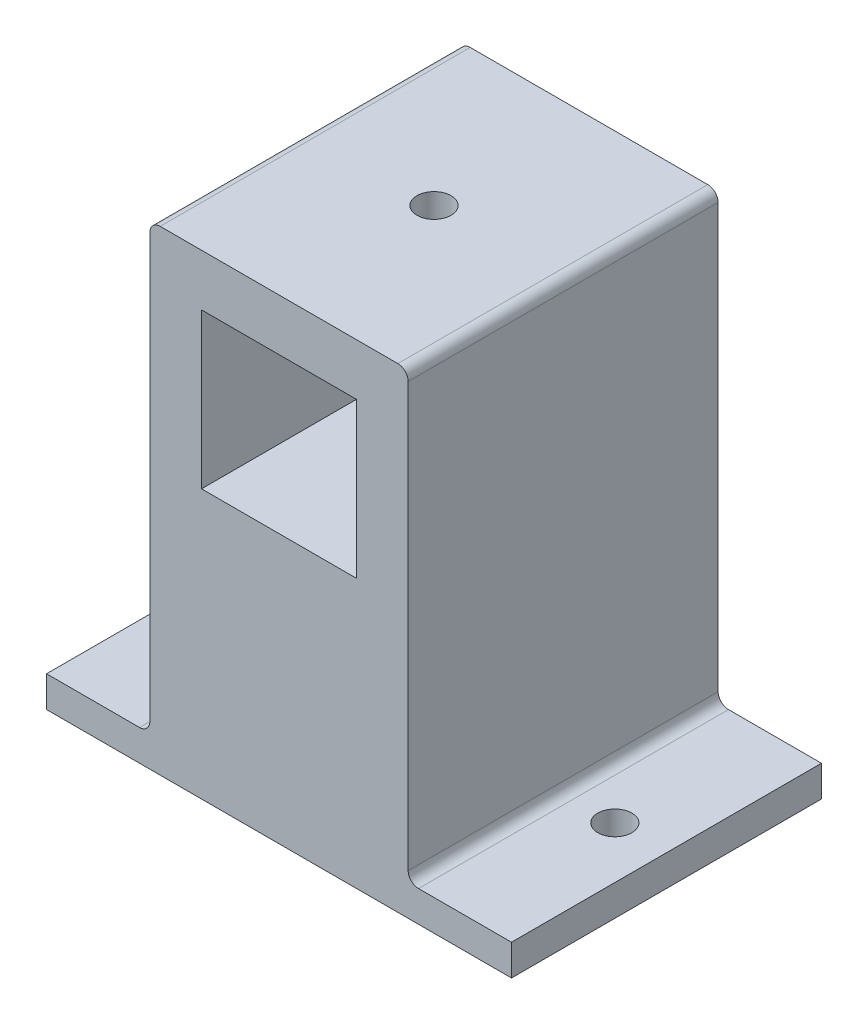
SolidWorks part; units mm, degrees
ref_plane "前视基准面" through (0, 0, 0) normal (0, 0, 1) x (1, 0, 0)
ref_plane "上视基准面" through (0, 0, 0) normal (0, 1, 0) x (1, 0, 0)
ref_plane "右视基准面" through (0, 0, 0) normal (1, 0, 0) x (0, 0, -1)
sketch "草图1" plane through (0, 0, 0) normal (0, 0, 1) x (1, 0, 0)
  line L1 (-7.5, -7.5) -> (7.5, -7.5)
  line L2 (-7.5, -7.5) -> (-7.5, 7.5)
  line L3 (-7.5, 7.5) -> (7.5, 7.5)
  line L4 (7.5, -7.5) -> (7.5, 7.5)
  line L5 (-7.5, -7.5) -> (7.5, 7.5) construction
  line L6 (-7.5, 7.5) -> (7.5, -7.5) construction
  line L7 (-12.5, -12.5) -> (12.5, -12.5)
  line L8 (-12.5, -12.5) -> (-12.5, 12.5)
  line L9 (-12.5, 12.5) -> (12.5, 12.5)
  line L10 (12.5, -12.5) -> (12.5, 12.5)
  line L11 (-12.5, -12.5) -> (12.5, 12.5) construction
  line L12 (-12.5, 12.5) -> (12.5, -12.5) construction
  point P0 (0, 0)
  point P6 (0, 0)
  dimension "D1" = 15
  dimension "D2" = 15
  dimension "D3" = 25
  dimension "D4" = 25
extrude "凸台-拉伸1" add sketch "草图1" along normal blind 30
sketch "草图2" plane through (0, 0, 30) normal (0, 0, 1) x (1, 0, 0)
  line L0 (0, 0) -> (0, -35.3965) construction
  line L2 (-12.5, -33.5) -> (12.5, -33.5)
  line L3 (-12.5, -33.5) -> (-12.5, -12.5)
  line L4 (-12.5, -12.5) -> (12.5, -12.5)
  line L5 (12.5, -33.5) -> (12.5, -12.5)
  line L6 (-12.5, -33.5) -> (12.5, -12.5) construction
  line L7 (-12.5, -12.5) -> (12.5, -33.5) construction
  line L8 (-22.5, -30.5) -> (22.5, -30.5)
  line L9 (-22.5, -30.5) -> (-22.5, -33.5)
  line L10 (-22.5, -33.5) -> (22.5, -33.5)
  line L11 (22.5, -30.5) -> (22.5, -33.5)
  line L12 (-22.5, -30.5) -> (22.5, -33.5) construction
  line L13 (-22.5, -33.5) -> (22.5, -30.5) construction
  point P3 (0, -23)
  point P9 (0, -32)
  line M8 (-12.5, -12.5) -> (12.5, -12.5)
  dimension "D1" = 21
  dimension "D2" = 3
  dimension "D3" = 45
extrude "凸台-拉伸2" add sketch "草图2" against normal blind 30 contours L3 L8 L5 M8 | L9 L10 L3 L8 | L3 L10 L5 L8 | L11 L8 L5 L10
sketch "草图3" plane through (0, -30.5, 0) normal (0, 1, 0) x (1, 0, 0)
  line L0 (12.5, -15) -> (22.5, -15) construction
  line L1 (12.5, 0) -> (12.5, -30) construction
  line L2 (22.5, 0) -> (22.5, -30) construction
  line L3 (17.5, 0) -> (17.5, -30) construction
  line L4 (12.5, 0) -> (22.5, 0) construction
  line L5 (12.5, -30) -> (22.5, -30) construction
  circle A0 centre (17.5, -15) radius 1.65
  dimension "D1" = 3.3
extrude "切除-拉伸1" cut sketch "草图3" against normal blind 30
mirror "镜向1" about plane through (0, 0, 0) normal (1, 0, 0) of "切除-拉伸1"
sketch "草图4" plane through (0, 12.5, 0) normal (0, 1, 0) x (1, 0, 0)
  line L0 (0, 0) -> (0, -30) construction
  line L1 (12.5, -30) -> (-12.5, -30) construction
  circle A0 centre (0, -15) radius 1.65
  dimension "D1" = 3.3
extrude "切除-拉伸2" cut sketch "草图4" against normal blind 1000
fillet "圆角1" radius 1 4 edges at (12.5, -30.5, 15) (12.5, 12.5, 15) (-12.5, 12.5, 15) (-12.5, -30.5, 15)
